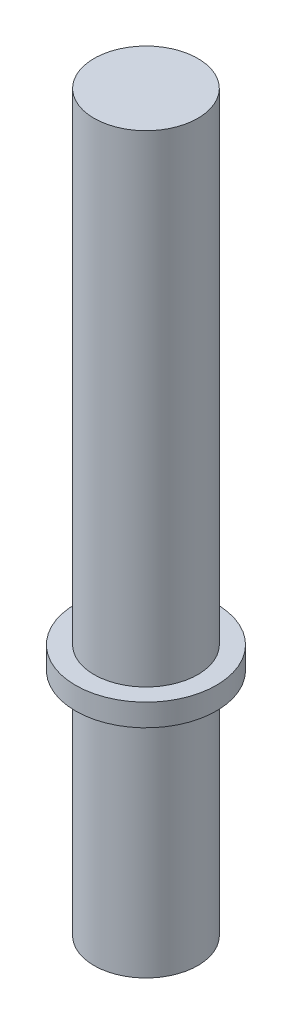
SolidWorks part; units mm, degrees
ref_plane "Front Plane" through (0, 0, 0) normal (0, 0, 1) x (1, 0, 0)
ref_plane "Top Plane" through (0, 0, 0) normal (0, 1, 0) x (1, 0, 0)
ref_plane "Right Plane" through (0, 0, 0) normal (1, 0, 0) x (0, 0, -1)
sketch "Sketch1" plane through (0, 0, 0) normal (0, 1, 0) x (1, 0, 0)
  circle A0 centre (0, 0) radius 7
  dimension "D1" = 14
extrude "Boss-Extrude1" add sketch "Sketch1" along normal blind 65 and the other way blind 34
sketch "Sketch2" plane through (0, 0, 0) normal (0, 1, 0) x (1, 0, 0)
  circle A0 centre (0, 0) radius 9.5
  dimension "D1" = 19
extrude "Boss-Extrude2" add sketch "Sketch2" against normal blind 3
